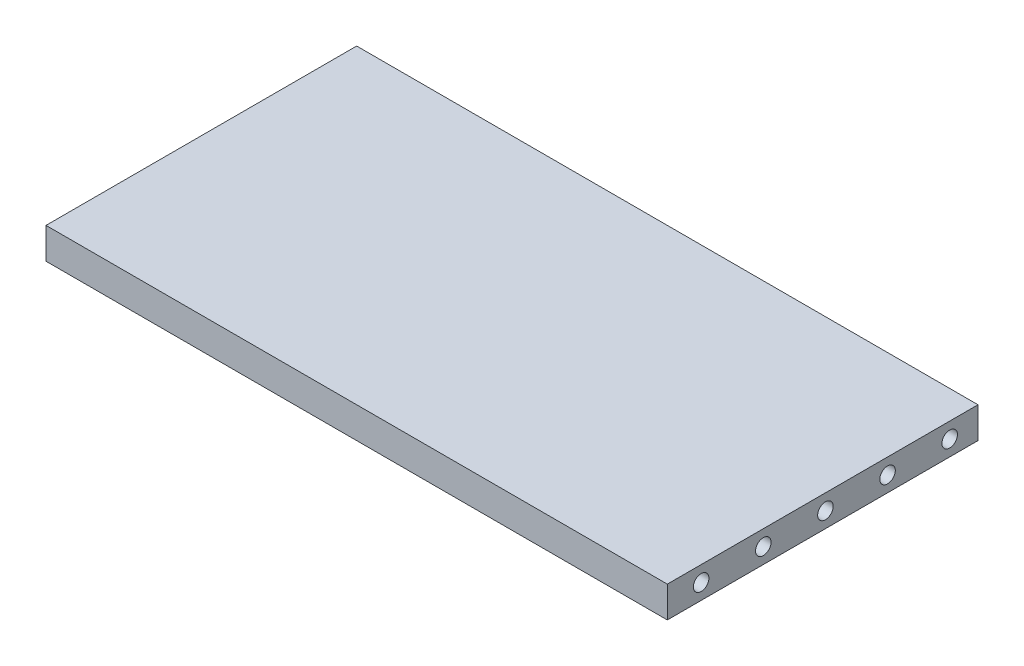
SolidWorks part; units mm, degrees
ref_plane "Front Plane" through (0, 0, 0) normal (0, 0, 1) x (1, 0, 0)
ref_plane "Top Plane" through (0, 0, 0) normal (0, 1, 0) x (1, 0, 0)
ref_plane "Right Plane" through (0, 0, 0) normal (1, 0, 0) x (0, 0, -1)
sketch "Sketch1" plane through (0, 0, 0) normal (0, 1, 0) x (1, 0, 0)
  line L1 (-63.5, -31.75) -> (63.5, -31.75)
  line L2 (-63.5, -31.75) -> (-63.5, 31.75)
  line L3 (-63.5, 31.75) -> (63.5, 31.75)
  line L4 (63.5, -31.75) -> (63.5, 31.75)
  line L5 (-63.5, -31.75) -> (63.5, 31.75) construction
  line L6 (-63.5, 31.75) -> (63.5, -31.75) construction
  point P0 (0, 0)
  dimension "D1" = 127
  dimension "D2" = 63.5
extrude "Boss-Extrude1" add sketch "Sketch1" along normal blind 6.35
ref_plane "Plane1" through (0, 0, 0) normal (0, 0, -1) x (-1, 0, 0)
ref_plane "Plane2" through (0, 0, 0) normal (0, 0, -1) x (-1, 0, 0)
sketch "Sketch2" plane through (-63.5, 0, 0) normal (-1, 0, 0) x (0, 0, 1)
  line L2 (-31.75, 6.35) -> (-31.75, 0) construction
  line L3 (-31.75, 3.175) -> (-22.1203, 3.175)
  circle A0 centre (-25.9629, 3.175) radius 1.5875
  dimension "D1" = 0
  dimension "D2" = 3.175
extrude "Cut-Extrude1" cut sketch "Sketch2" against normal up to next contours A0
pattern_linear "LPattern1" count 5 spacing 12.7 along (0, 0, 1) of "Cut-Extrude1"
